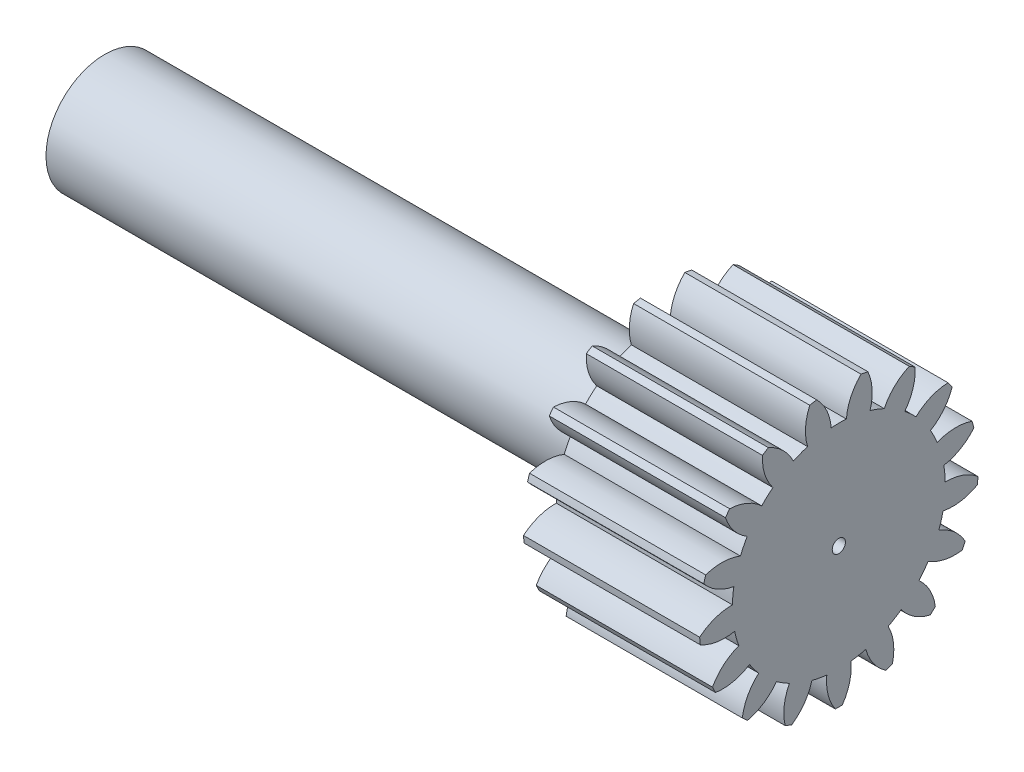
SolidWorks part; units mm, degrees
ref_plane "Plane1" through (0, 0, 0) normal (0, 0, 1) x (1, 0, 0)
ref_plane "Plane2" through (0, 0, 0) normal (0, 1, 0) x (1, 0, 0)
ref_plane "Plane3" through (0, 0, 0) normal (1, 0, 0) x (0, 0, -1)
other "Configuration Table"
sketch "HoldingSke" plane through (0, 0, 0) normal (0, 1, 0) x (1, 0, 0)
  line L0 (0, 0) -> (0.9563, -0.2924)
  line L1 (-15, 0) -> (100, 0) construction
  line L2 (0, 0) -> (-2.1039, 2.3779)
  line L3 (0, 0) -> (-11.863, 4.5341)
  line L4 (0, 0) -> (8.2586, 2.5249)
  line L5 (0, 0) -> (-46.8476, -17.4728)
  line L6 (0, 0) -> (-9.9476, -6.7116)
  line L7 (-2.1039, 2.3779) -> (8.6586, 51.2059)
  line L8 (-76.2, 54.61) -> (-76.1, 54.61)
  line L9 (-71.009, 38.7566) -> (-53.1078, 45.2721)
  line L10 (-76.2, 71.12) -> (104.1128, 71.12)
  line L11 (0, 0) -> (-12, 0)
  line L12 (-76.2, 101.6) -> (-76.162, 101.6)
  line L13 (24.9733, 27.94) -> (52.9518, 28.4284)
  line L14 (24.9733, 27.94) -> (24.9743, 27.94)
  line L15 (24.9733, 27.94) -> (100.4006, 29.5858)
  line L16 (-63.627, -1) -> (-12.827, -1)
  circle A0 centre (0, 0) radius 0.45
  circle A1 centre (0, 0) radius 4
  circle A2 centre (0, 0) radius 4
  circle A3 centre (0, 0) radius 0.45
  dimension "MHD" = 8
  dimension "Hub_dia" = 8
  dimension "Bore" = 0.9
  dimension "MBD" = 0.9
  dimension "Num_teeth" = 17
  dimension "Pitch" = 1
  dimension "Overall_len" = 50
  dimension "Show_teeth" = 17
  dimension "Thickness" = 12
  dimension "OAL" = 50.0001
  dimension "T_dim" = 0.1
  dimension "Ap" = 20
  dimension "H" = 19.05
  dimension "Pitch_radius" = 180.3128
  dimension "Width" = 12
  dimension "Backlash" = 0.038
  dimension "Addendum_fac" = 1
  dimension "Dedendum_fac" = 1.25
  dimension "Clearance_fac" = 0.25
  dimension "Dedendum_add" = 0.001
  dimension "Module" = 1
sketch "BasProSke" plane through (0, 0, 0) normal (0, 1, 0) x (1, 0, 0)
  line L0 (-10, 0) -> (60, 0) construction
  line L1 (0, 0) -> (0, 9.5)
  line L2 (0, 0) -> (12, 0)
  line L3 (12, 0) -> (12, 9.5)
  line L4 (12, 9.5) -> (0, 9.5)
  dimension "Thickness" = 12
  dimension "Diameter" = 19
revolve "Base-Revolve" add sketch "BasProSke" angle 360 about L0
sketch "TooCutSke" plane through (0, 0, 0) normal (1, 0, 0) x (0, 0, -1)
  line L1 (0, 0) -> (0, 107) construction
  line L2 (0, 0) -> (-0.8507, 8.4573) construction
  line L3 (0, 0) -> (-3.1126, 16.6509) construction
  line L4 (-0.8507, 8.4573) -> (-1.5563, 8.3254) construction
  arc A0 (0.5169, 7.2306) -> (-0.5169, 7.2306) centre (0, 0) ccw
  arc A1 (1.5331, 9.4012) -> (-1.5331, 9.4012) centre (0, 0) ccw
  circle A2 centre (0, 0) radius 8.5 construction
  circle A3 centre (0, 0) radius 7.9874 construction
  arc A4 (-0.5169, 7.2306) -> (-1.5331, 9.4012) centre (-3.9066, 6.9668) ccw
  arc A5 (1.5331, 9.4012) -> (0.5169, 7.2306) centre (3.9066, 6.9668) ccw
  dimension "Root_dia" = 14.498
  dimension "Overcut_dia" = 19.0508
  dimension "Pitch_dia" = 17
  dimension "Base_dia" = 15.9748
  dimension "Flank_rad" = 3.4
  dimension "Half_ang" = 10.588
  dimension "Half_CT" = 0.7178
extrude "ToothCut" cut sketch "TooCutSke" along normal through all
fillet "Breaks" [suppressed] radius 0.02
fillet "RootFillets" [suppressed] radius 0.251
pattern_circular "TeethCuts" count 17 every 21.176 about axis through (-10, 0, 0) along (1, 0, 0) of "ToothCut", "RootFillets", "Breaks"
sketch "HubNeaOneSke" plane through (0, 0, 0) normal (-1, 0, 0) x (0, 0, 1)
  circle A0 centre (0, 0) radius 4
  dimension "Diameter" = 8
extrude "HubNearOne" add sketch "HubNeaOneSke" along normal blind 38.0001
sketch "HubNeaBotSke" plane through (0, 0, 0) normal (-1, 0, 0) x (0, 0, 1)
  circle A0 centre (0, 0) radius 4
  dimension "Diameter" = 8
extrude "HubNearBoth" [suppressed] add sketch "HubNeaBotSke" along normal blind 19
ref_plane "FarPln" through (12, 0, 0) normal (1, 0, 0) x (0, 0, -1)
sketch "HubFarSke" plane through (12, 0, 0) normal (1, 0, 0) x (0, 0, -1)
  circle A0 centre (0, 0) radius 4
  dimension "Diameter" = 8
extrude "HubFar" [suppressed] add sketch "HubFarSke" along normal blind 19
sketch "BorSke" plane through (0, 0, 0) normal (1, 0, 0) x (0, 0, -1)
  circle A0 centre (0, 0) radius 0.45
  dimension "Diameter" = 0.9
extrude "Bore" cut sketch "BorSke" along normal mid plane 100.0001
sketch "KeySke" plane through (0, 0, 0) normal (1, 0, 0) x (0, 0, -1)
  line L0 (-0.05, 0) -> (-0.05, 0.55)
  line L1 (-0.05, 0.55) -> (0.05, 0.55)
  line L2 (0.05, 0.55) -> (0.05, 0)
  line L3 (0, 0) -> (0, 34) construction
  line L4 (-0.05, 0) -> (0.05, 0)
  dimension "Offset" = 0.55
  dimension "Width" = 0.1
extrude "Keyway" [suppressed] cut sketch "KeySke" along normal mid plane 100.0001
pattern_circular "Keyway2" [suppressed] count 2 every 90 about axis through (-10, 0, 0) along (1, 0, 0)
equation "' \"Module@HoldingSke\" = 6.35"
equation "' \"Num_teeth@HoldingSke\" = 12"
equation "' \"Ap@HoldingSke\" =  20"
equation "' \"Ap@HoldingSke\" = 20"
equation "' \"Width@HoldingSke\" = 0.5 * 25.4"
equation "' \"Hub_dia@HoldingSke\"= 1 * 25.4"
equation "' \"Hub_dia@HoldingSke\" = 1 * 25.4"
equation "' \"Overall_len@HoldingSke\" = 1.0 * 25.4"
equation "' \"Bore@HoldingSke\" = 0.75 * 25.4"
equation "' \"T_dim@HoldingSke\" = 0.1 * 25.4"
equation "' \"Width@KeySke\" = 0.25 * 25.4"
equation "' \"Show_teeth@HoldingSke\" = 13"
equation "' \"Backlash@HoldingSke\" = 0.009 * 25.4"
equation "' \"Addendum_fac@HoldingSke\" = 1.0"
equation "' \"Dedendum_fac@HoldingSke\" = 1.25"
equation "' \"Dedendum_add@HoldingSke\" = 0.00005 * 25.4"
equation "' \"Clearance_fac@HoldingSke\" = 0.25"
equation "\"Pitch@HoldingSke\" = 1 / \"Module@HoldingSke\""
equation "\"Overcut_dia@TooCutSke\" = (\"Num_teeth@HoldingSke\" + 2 * \"Addendum_fac@HoldingSke\") / \"Pitch@HoldingSke\" + 0.002 * 25.4"
equation "\"Pitch_dia@TooCutSke\" = \"Num_teeth@HoldingSke\" / \"Pitch@HoldingSke\""
equation "\"Base_dia@TooCutSke\" = \"Num_teeth@HoldingSke\" / \"Pitch@HoldingSke\" * cos((\"Ap@HoldingSke\"  * 3.14159265 / 180))"
equation "\"Root_dia@TooCutSke\" = (\"Num_teeth@HoldingSke\" + 2) / \"Pitch@HoldingSke\" - 2 * (\"Addendum_fac@HoldingSke\" + \"Dedendum_fac@HoldingSke\") / \"Pitch@HoldingSke\" - \"Dedendum_add@HoldingSke\" * 2"
equation "\"Half_ang@TooCutSke\" = 180 / \"Num_teeth@HoldingSke\""
equation "\"Half_CT@TooCutSke\" = \"Num_teeth@HoldingSke\" / \"Pitch@HoldingSke\" * sin((3.14159265 / 2 / \"Num_teeth@HoldingSke\")) / 2 - 7 * \"Backlash@HoldingSke\" / 4"
equation "\"Flank_rad@TooCutSke\" = \"Num_teeth@HoldingSke\" / \"Pitch@HoldingSke\" / 5"
equation "\"Radius@RootFillets\" = \"Clearance_fac@HoldingSke\" / \"Pitch@HoldingSke\" + \"Dedendum_add@HoldingSke\""
equation "\"Break_rad@Breaks\" = 0.02 / \"Pitch@HoldingSke\""
equation "\"Thickness@HoldingSke\" = \"Width@HoldingSke\""
equation "\"OAL@HoldingSke\" = \"Thickness@HoldingSke\""
equation "\"MHD@HoldingSke\" = (\"Num_teeth@HoldingSke\" + 2) / \"Pitch@HoldingSke\" - 2 * (\"Addendum_fac@HoldingSke\" + \"Dedendum_fac@HoldingSke\")  / \"Pitch@HoldingSke\" - \"Dedendum_add@HoldingSke\" * 2"
equation "\"MBD@HoldingSke\" = (\"Num_teeth@HoldingSke\" + 2) / \"Pitch@HoldingSke\" - 2 * (\"Addendum_fac@HoldingSke\" + \"Dedendum_fac@HoldingSke\")  / \"Pitch@HoldingSke\" - \"Dedendum_add@HoldingSke\" * 2 - 0.002 * 25.4"
equation "\"MHD@HoldingSke\" = ((sgn( \"MHD@HoldingSke\" - \"Hub_dia@HoldingSke\" )-1)*( \"MHD@HoldingSke\" - \"Hub_dia@HoldingSke\" ))/-2+ \"Hub_dia@HoldingSke\""
equation "\"MBD@HoldingSke\" = ((sgn( \"MBD@HoldingSke\" - \"Bore@HoldingSke\" )-1)*( \"MBD@HoldingSke\" - \"Bore@HoldingSke\" ))/-2+ \"Bore@HoldingSke\""
equation "\"OAL@HoldingSke\" = ((sgn( \"OAL@HoldingSke\" - \"Overall_len@HoldingSke\" )+1)*( \"OAL@HoldingSke\" - \"Overall_len@HoldingSke\" ))/2 + \"Overall_len@HoldingSke\" + 0.000002 * 25.4"
equation "\"Num_teeth@TeethCuts\" = int( \"Show_teeth@HoldingSke\" ) + 1"
equation "\"Num_teeth@TeethCuts\" = ((sgn( \"Num_teeth@TeethCuts\" - \"Num_teeth@HoldingSke\" )-1)*( \"Num_teeth@TeethCuts\" - \"Num_teeth@HoldingSke\" ))/-2+ \"Num_teeth@HoldingSke\""
equation "\"Num_teeth@TeethCuts\" = ((sgn( \"Num_teeth@TeethCuts\" - 2.0)+1)*( \"Num_teeth@TeethCuts\" - 2.0))/2 +2.0"
equation "\"Angle@TeethCuts\" = 360.0 / \"Num_teeth@HoldingSke\""
equation "\"Diameter@BasProSke\" = (\"Num_teeth@HoldingSke\" + 2 * \"Addendum_fac@HoldingSke\") / \"Pitch@HoldingSke\""
equation "\"Thickness@BasProSke\"  = \"Thickness@HoldingSke\""
equation "' \"Fillet_rad@BasProSke\" =  \"Thickness@HoldingSke\" * 0.05"
equation "' \"Fillet_rad@BasProSke\" = \"Thickness@HoldingSke\" * 0.05"
equation "\"MHD@HoldingSke\" = ((sgn( \"MHD@HoldingSke\" - \"Root_dia@TooCutSke\" )-1)*( \"MHD@HoldingSke\" - \"Root_dia@TooCutSke\" ))/-2+ \"Root_dia@TooCutSke\""
equation "\"Diameter@HubNeaOneSke\" = \"MHD@HoldingSke\""
equation "\"Length@HubNearOne\" = \"OAL@HoldingSke\" - \"Thickness@BasProSke\""
equation "\"Diameter@HubNeaBotSke\" = \"MHD@HoldingSke\""
equation "\"Length@HubNearBoth\" = ( \"OAL@HoldingSke\" - \"Thickness@BasProSke\" ) / 2.0"
equation "\"Thickness@FarPln\" = \"Thickness@BasProSke\""
equation "\"Diameter@HubFarSke\" = \"MHD@HoldingSke\""
equation "\"Length@HubFar\" = ( \"OAL@HoldingSke\" - \"Thickness@BasProSke\" ) / 2.0"
equation "\"Diameter@BorSke\" = \"MBD@HoldingSke\""
equation "\"D1@Bore\" = \"OAL@HoldingSke\" * 2.0"
equation "\"D1@Keyway\" = \"OAL@HoldingSke\" * 2.0"
equation "\"Offset@KeySke\" = \"T_dim@HoldingSke\" + \"MBD@HoldingSke\" / 2.0"
